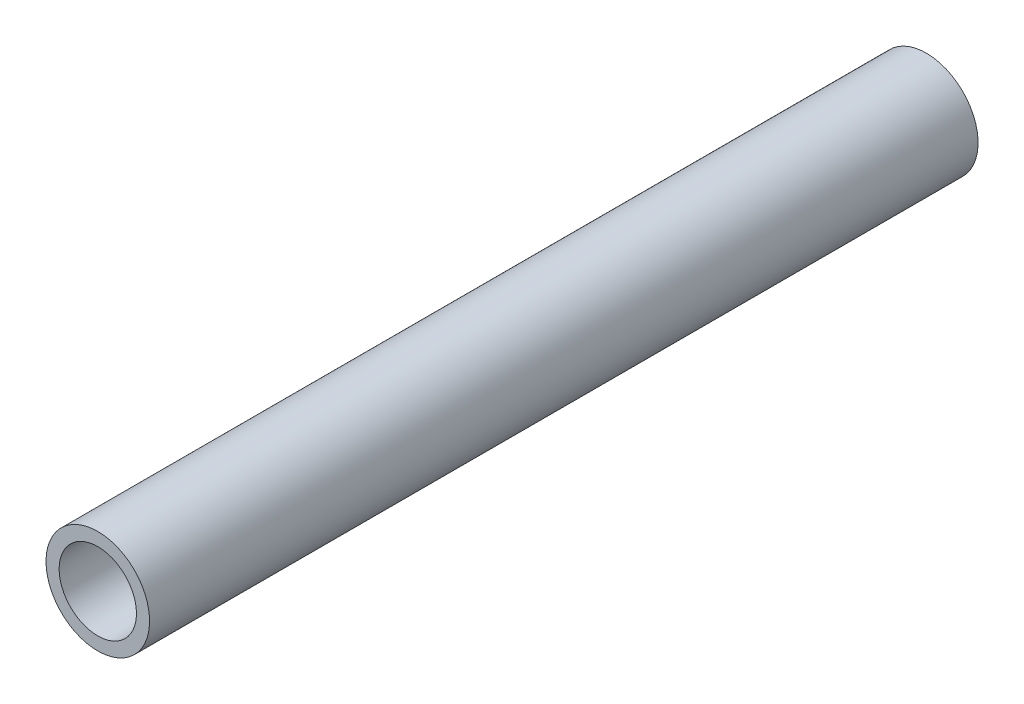
SolidWorks part; units mm, degrees
ref_plane "Front Plane" through (0, 0, 0) normal (0, 0, 1) x (1, 0, 0)
ref_plane "Top Plane" through (0, 0, 0) normal (0, 1, 0) x (1, 0, 0)
ref_plane "Right Plane" through (0, 0, 0) normal (1, 0, 0) x (0, 0, -1)
sketch "Sketch1" plane through (0, 0, 0) normal (0, 0, 1) x (1, 0, 0)
  circle A0 centre (0, 0) radius 9.525
  circle A1 centre (0, 0) radius 7.112
  dimension "D1" = 2.413
  dimension "D2" = 19.05
extrude "Boss-Extrude1" add sketch "Sketch1" along normal blind 152.4
